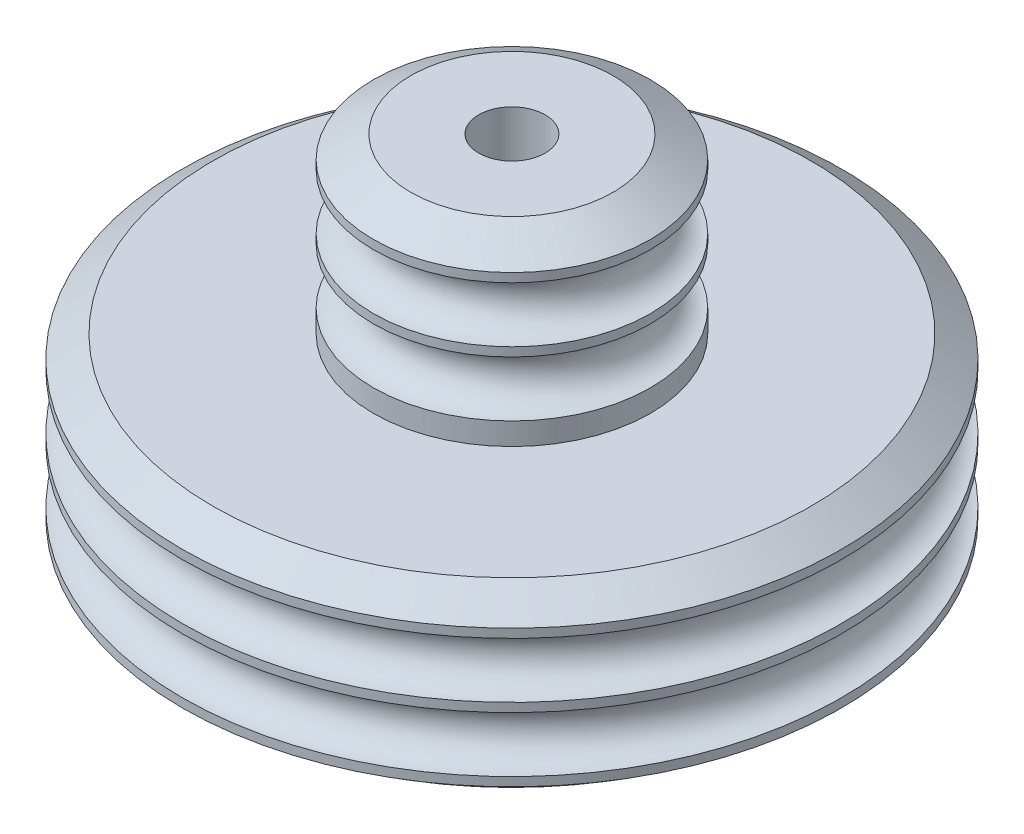
SolidWorks part; units mm, degrees
ref_plane "Front Plane" through (0, 0, 0) normal (0, 0, 1) x (1, 0, 0)
ref_plane "Top Plane" through (0, 0, 0) normal (0, 1, 0) x (1, 0, 0)
ref_plane "Right Plane" through (0, 0, 0) normal (1, 0, 0) x (0, 0, -1)
sketch "Sketch1" plane through (0, 0, 0) normal (0, 0, 1) x (1, 0, 0)
  line L0 (0, 20.8135) -> (0, 0) construction
  line L1 (-3, -0.2927) -> (-12.5, -0.2927)
  line L2 (-26.9984, -0.2927) -> (-29.75, 1.7073)
  line L3 (-29.75, 1.7073) -> (-29.75, 2.5073)
  line L4 (-29.75, 7.5073) -> (-29.75, 8.3073)
  line L5 (-29.75, 7.9073) -> (0, 7.9073) construction
  line L6 (-29.75, 14.1073) -> (-29.75, 13.3073)
  line L7 (-23.9984, -0.2927) -> (-20.75, 5.7073)
  line L8 (-20.75, 5.7073) -> (-15.75, 5.7073)
  line L9 (-15.75, 5.7073) -> (-12.5, -0.2927)
  line L10 (-23.9984, -0.2927) -> (-26.9984, -0.2927)
  line L11 (-29.75, 14.1073) -> (-27, 16.1073)
  line L12 (-27, 16.1073) -> (-12.5, 16.1073)
  line L13 (-12.5, 16.1073) -> (-12.5, 18.1073)
  line L14 (-12.5, 23.1073) -> (-12.5, 23.9073)
  line L15 (-12.5, 28.9073) -> (-12.5, 29.7073)
  line L16 (-12.5, 29.7073) -> (-9.1319, 31.7073)
  line L17 (-9.1319, 31.7073) -> (-3, 31.7073)
  line L18 (-3, 31.7073) -> (-3, -0.2927)
  arc A0 (-29.75, 2.5073) -> (-29.75, 7.5073) centre (-29.75, 5.0073) ccw
  arc A1 (-29.75, 13.3073) -> (-29.75, 8.3073) centre (-29.75, 10.8073) cw
  arc A2 (-12.5, 18.1073) -> (-12.5, 23.1073) centre (-12.5, 20.6073) ccw
  arc A3 (-12.5, 23.9073) -> (-12.5, 28.9073) centre (-12.5, 26.4073) ccw
  point P22 (-25.0037, 0.6009)
  point P29 (-24.6841, -0.2927)
  point P31 (-23.0262, 3.4122)
  point P33 (-17.9414, 3.4727)
  dimension "D1" = 5
  dimension "D8" = 5
  dimension "D9" = 5
  dimension "D2" = 29.75
  dimension "D3" = 0.8
  dimension "D4" = 0.4
  dimension "D5" = 27
  dimension "D6" = 2
  dimension "D7" = 0.8
  dimension "D10" = 2
  dimension "D11" = 2
  dimension "D12" = 12.5
  dimension "D13" = 2
  dimension "D14" = 0.8
  dimension "D15" = 3
  dimension "D16" = 12.5
  dimension "D17" = 3
  dimension "D18" = 6
  dimension "D19" = 5
  dimension "D20" = 3.25
revolve "Revolve1" add sketch "Sketch1" angle 360 about L0
